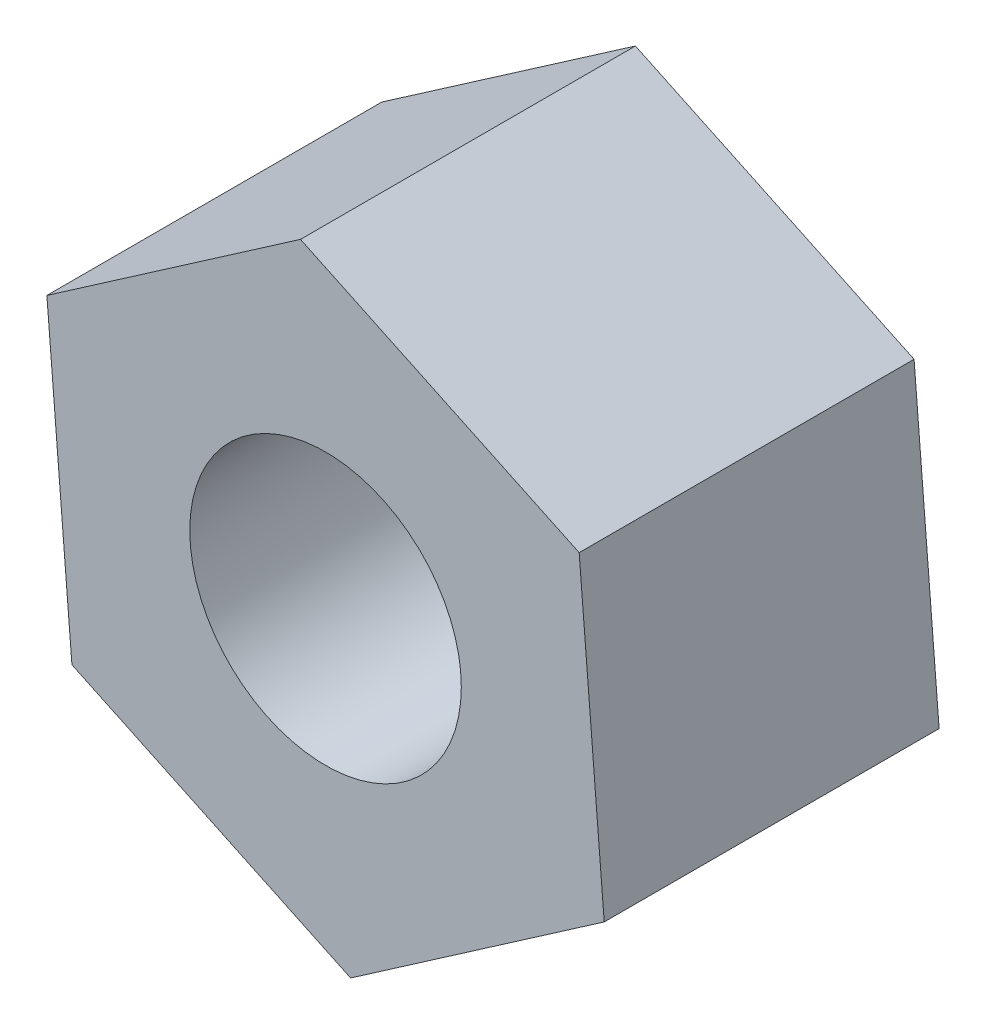
SolidWorks part; units mm, degrees
ref_plane "Plan de face" through (0, 0, 0) normal (0, 0, 1) x (1, 0, 0)
ref_plane "Plan de dessus" through (0, 0, 0) normal (0, 1, 0) x (1, 0, 0)
ref_plane "Plan de droite" through (0, 0, 0) normal (1, 0, 0) x (0, 0, -1)
sketch "Esquisse1" plane through (0, 0, 0) normal (0, 0, 1) x (1, 0, 0)
  line L1 (-0.2767, 3.3951) -> (-3.0786, 1.4579)
  line L2 (-3.0786, 1.4579) -> (-2.8019, -1.9372)
  line L3 (-2.8019, -1.9372) -> (0.2767, -3.3951)
  line L4 (0.2767, -3.3951) -> (3.0786, -1.4579)
  line L5 (3.0786, -1.4579) -> (2.8019, 1.9372)
  line L6 (2.8019, 1.9372) -> (-0.2767, 3.3951)
  circle A0 centre (0, 0) radius 1.5
  circle A1 centre (0, 0) radius 2.95 construction
  dimension "D1" = 3
  dimension "D2" = 5.9
extrude "Boss.-Extru.1" add sketch "Esquisse1" along normal blind 3.7
cosmetic thread "Représentation de filetage1" parameters "D2"=4
